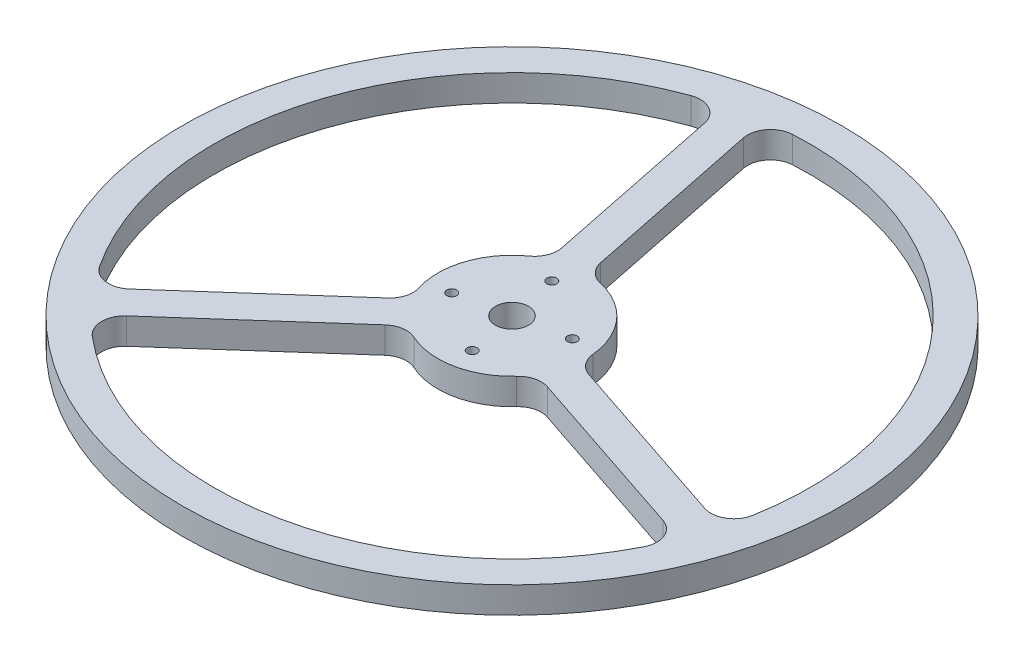
SolidWorks part; units mm, degrees
ref_plane "前视基准面" through (0, 0, 0) normal (0, 0, 1) x (1, 0, 0)
ref_plane "上视基准面" through (0, 0, 0) normal (0, 1, 0) x (1, 0, 0)
ref_plane "右视基准面" through (0, 0, 0) normal (1, 0, 0) x (0, 0, -1)
other "Configuration Table"
sketch "草图1" plane through (0, 0, 0) normal (0, 1, 0) x (1, 0, 0)
  line L0 (-4.5062, 22.0441) -> (-18.101, 88.5482) construction
  line L3 (-22.9719, 87.4112) -> (-9.2923, 20.4916)
  line L4 (-13.1745, 89.414) -> (0.5051, 22.4943)
  line L5 (22.3923, -2.1984) -> (87.1863, -23.8113)
  line L6 (19.2281, -11.6846) -> (84.0221, -33.2975)
  line L7 (-70.8475, -56.1165) -> (-19.7332, -10.8097)
  line L8 (-64.2144, -63.5999) -> (-13.1001, -18.2931)
  circle A0 centre (0, 0) radius 100
  arc A1 (-9.2923, 20.4916) -> (-19.7332, -10.8097) centre (0, 0) ccw
  arc A2 (-22.9719, 87.4112) -> (-70.8475, -56.1165) centre (0, 0) ccw
  arc A3 (-13.1001, -18.2931) -> (19.2281, -11.6846) centre (0, 0) ccw
  arc A4 (22.3923, -2.1984) -> (0.5051, 22.4943) centre (0, 0) ccw
  arc A5 (87.1863, -23.8113) -> (-13.1745, 89.414) centre (0, 0) ccw
  arc A6 (-64.2144, -63.5999) -> (84.0221, -33.2975) centre (0, 0) ccw
  dimension "D3" = 5
  dimension "D4" = 5
extrude "凸台-拉伸2" add sketch "草图1" along normal blind 8
sketch "草图3" plane through (0, 8, 0) normal (0, 1, 0) x (1, 0, 0)
  line L0 (0, 0) -> (-20.0278, 97.9739) construction
  line L1 (-13.1745, 89.414) -> (0.5051, 22.4943) construction
  line L2 (-9.2923, 20.4916) -> (-22.9719, 87.4112) construction
  circle A0 centre (0, 0) radius 5
  circle A1 centre (-3.1043, 15.186) radius 1.5
  circle A2 centre (0, 0) radius 100 construction
  circle A3 centre (15.186, 3.1043) radius 1.5
  circle A4 centre (3.1043, -15.186) radius 1.5
  circle A5 centre (-15.186, -3.1043) radius 1.5
  point P21 (0, 0)
  dimension "D1" = 0
  dimension "D2" = 15.5
  dimension "D3" = 4
extrude "切除-拉伸1" cut sketch "草图3" against normal through all
fillet "圆角1" radius 7 6 edges at (-13.1745, 4, -89.414) (-22.9719, 4, -87.4112) (-70.8475, 4, 56.1165) (-64.2144, 4, 63.5999) (84.0221, 4, 33.2975) (87.1863, 4, 23.8113)
fillet "圆角2" radius 7 6 edges at (-13.1001, 4, 18.2931) (19.2281, 4, 11.6846) (22.3923, 4, 2.1984) (0.5051, 4, -22.4943) (-9.2923, 4, -20.4916) (-19.7332, 4, 10.8097)
